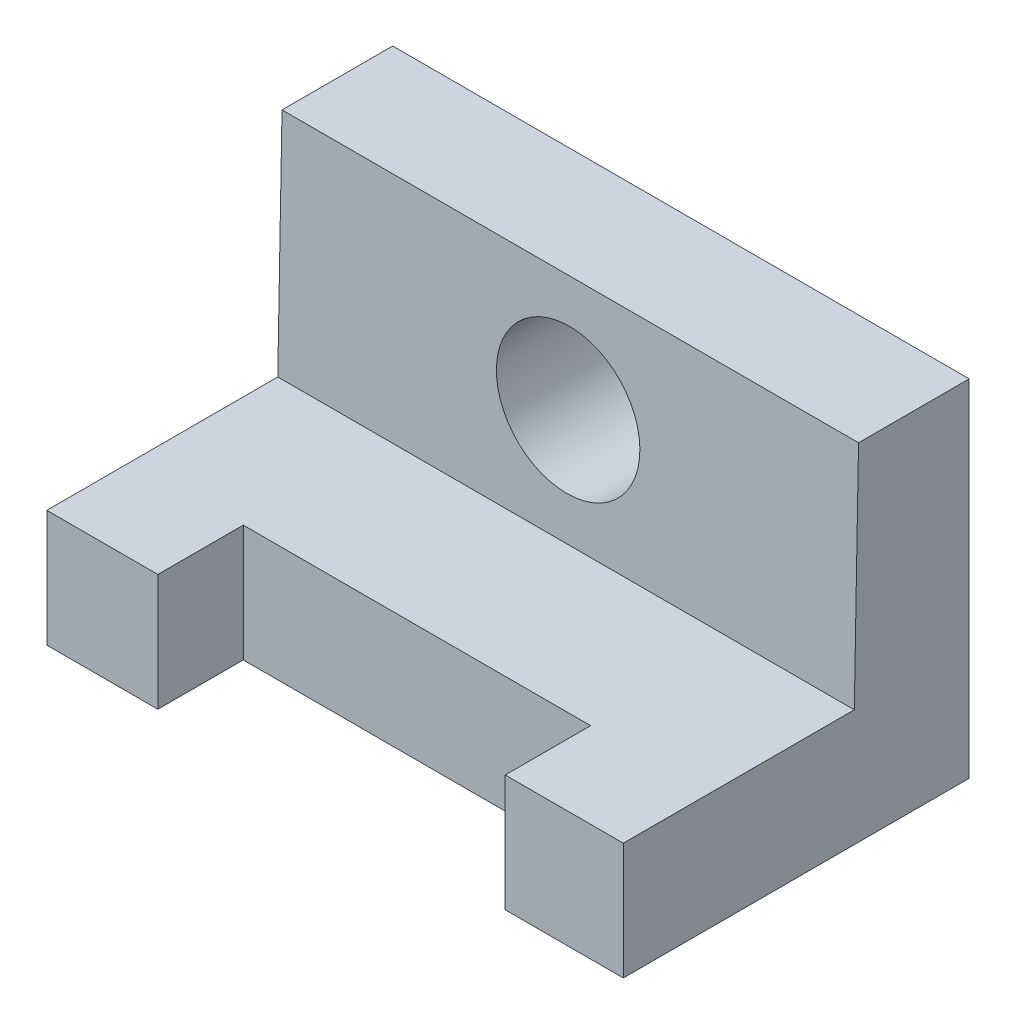
SolidWorks part; units mm, degrees
ref_plane "Front Plane" through (0, 0, 0) normal (0, 0, 1) x (1, 0, 0)
ref_plane "Top Plane" through (0, 0, 0) normal (0, 1, 0) x (1, 0, 0)
ref_plane "Right Plane" through (0, 0, 0) normal (1, 0, 0) x (0, 0, -1)
sketch "Sketch2" plane through (0, 0, 0) normal (1, 0, 0) x (0, 0, -1)
  line L0 (0, 0) -> (0, -60)
  line L1 (0, -60) -> (-60, -60)
  line L2 (-60, -60) -> (-60, -39.7469)
  line L3 (-60, -39.7469) -> (-19.9354, -39.7469)
  line L4 (-19.9354, -39.7469) -> (-19.1981, 0)
  line L5 (-19.1981, 0) -> (0, 0)
  dimension "D1" = 60
  dimension "D2" = 39.7537
  dimension "D3" = 40.0646
  dimension "D4" = 60
  dimension "D5" = 20.2531
extrude "Boss-Extrude1" add sketch "Sketch2" along normal blind 100 contours L5 L0 L1 L2 L3 L4
sketch "Sketch5" plane through (0, 0.356, 19.1915) normal (0, 0.0185, 0.9998) x (1, 0, 0)
  line L0 (0, -20.2329) -> (100, -20.2329) construction
  line L1 (0, -40.1098) -> (0, -0.3561) construction
  line L2 (100, -40.1098) -> (100, -0.3561) construction
  line L3 (100, -0.3561) -> (0, -0.3561) construction
  line L4 (100, -40.1098) -> (0, -40.1098) construction
  line L5 (50, -0.3561) -> (50, -40.1098) construction
  line L8 (-4.0619, -66.8464) -> (58.3658, -66.8464)
  line L9 (-4.0619, -66.8464) -> (-4.0619, -86.8951)
  line L10 (-4.0619, -86.8951) -> (58.3658, -86.8951)
  line L11 (58.3658, -66.8464) -> (58.3658, -86.8951)
  circle A0 centre (50, -20.2329) radius 12.443
  point P10 (50, -40.1098)
  point P15 (-4.0619, -66.8464)
extrude "Cut-Extrude1" cut sketch "Sketch5" against normal blind 100
sketch "Sketch6" plane through (0, -39.7469, 0) normal (0, 1, 0) x (1, 0, 0)
  line L5 (14.5479, -43.8052) -> (14.5479, -43.3821)
  line L6 (100, -60) -> (0, -60) construction
  line L7 (19.2658, -60) -> (79.5163, -60)
  line L8 (19.2658, -60) -> (19.2658, -45.184)
  line L9 (19.2658, -45.184) -> (79.5163, -45.184)
  line L10 (79.5163, -60) -> (79.5163, -45.184)
extrude "Cut-Extrude2" cut sketch "Sketch6" against normal blind 100 contours L7 L10 L9 L8
